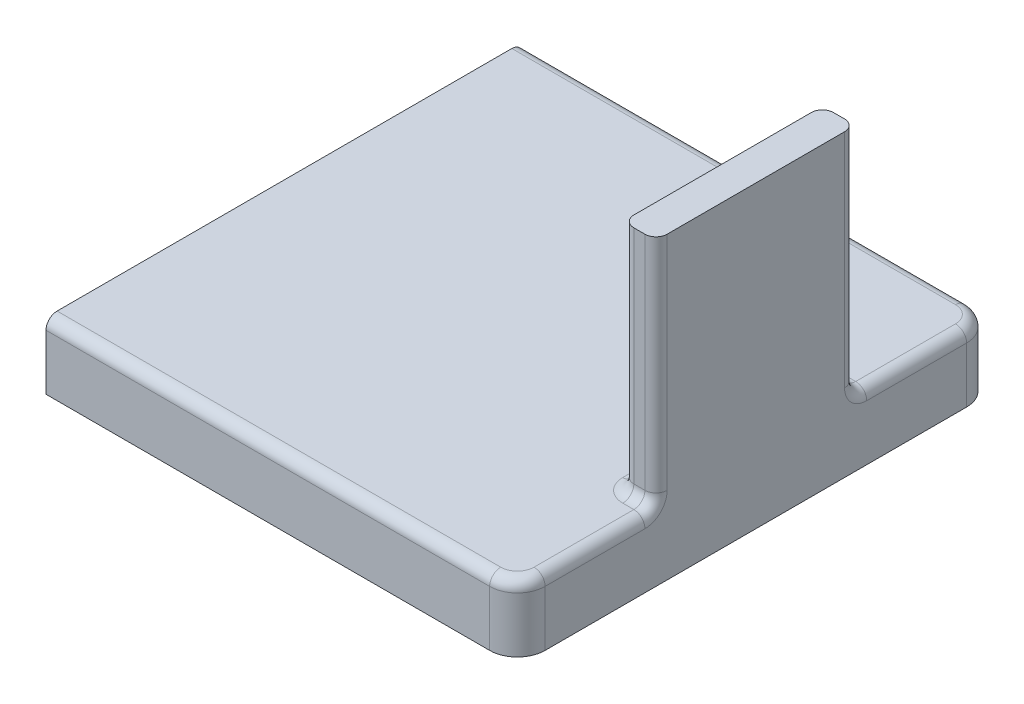
SolidWorks part; units mm, degrees
ref_plane "前基準面" through (0, 0, 0) normal (0, 0, 1) x (1, 0, 0)
ref_plane "上基準面" through (0, 0, 0) normal (0, 1, 0) x (1, 0, 0)
ref_plane "右基準面" through (0, 0, 0) normal (1, 0, 0) x (0, 0, -1)
sketch "草圖1" plane through (0, 0, 0) normal (0, 0, 1) x (1, 0, 0)
  line L0 (0, 0) -> (79, 0) construction
  line L1 (0, 0) -> (0, -42) construction
  line L2 (0, -42) -> (0, -54)
  line L3 (0, -54) -> (85, -54)
  line L4 (85, -42) -> (85, -54)
  line L7 (85, -42) -> (0, -42)
  dimension "D1" = 12
  dimension "D2" = 54
  dimension "D3" = 85
extrude "伸長1" add sketch "草圖1" along normal mid plane 86
sketch "草圖2" plane through (0, -54, 0) normal (0, -1, 0) x (1, 0, 0)
  line L8 (6, -37) -> (79, -37)
  line L9 (79, -37) -> (79, 37)
  line L10 (79, 37) -> (6, 37)
  line L11 (6, 37) -> (6, -37)
  line L12 (6, -37) -> (79, -37)
  line L13 (79, -37) -> (79, 37)
  line L14 (79, 37) -> (6, 37)
  line L15 (6, 37) -> (6, -37)
  dimension "D1" = 6
sketch "草圖3" plane through (0, 0, 0) normal (0, 0, 1) x (1, 0, 0)
  line L0 (85, -42) -> (85, 0)
  line L1 (85, 0) -> (79, 0)
  line L2 (79, 0) -> (79, -42)
  line L3 (85, -42) -> (0, -42) construction
  line L4 (79, -42) -> (85, -42)
  dimension "D1" = 6
extrude "伸長3" add sketch "草圖3" along normal mid plane 36
fillet "圓角1" radius 5 2 edges at (85, -48, -43) (85, -48, 43)
fillet "圓角2" radius 2 13 edges at (40, -42, -43) (83.5355, -42, -41.5355) (79, -42, 0) (40, -42, 43) (83.5355, -42, 41.5355) (79, -21, -18) (79, -21, 18)
